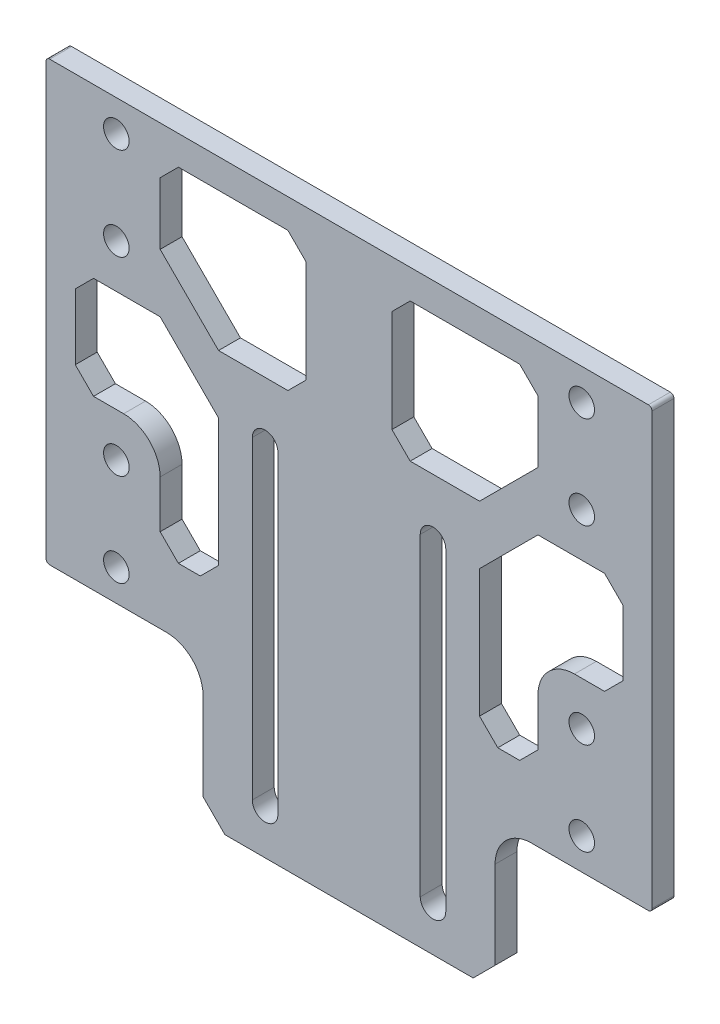
SolidWorks part; units mm, degrees
ref_plane "Plano frontal" through (0, 0, 0) normal (0, 0, 1) x (1, 0, 0)
ref_plane "Plano superior" through (0, 0, 0) normal (0, 1, 0) x (1, 0, 0)
ref_plane "Plano direito" through (0, 0, 0) normal (1, 0, 0) x (0, 0, -1)
sketch "Esboço1" plane through (0, 0, 0) normal (0, 0, 1) x (1, 0, 0)
  line L28 (-83, -60) -> (83, -60)
  line L29 (-83, -60) -> (-83, 60)
  line L30 (-83, 60) -> (83, 60)
  line L31 (83, -60) -> (83, 60)
  line L32 (-83, -60) -> (83, 60) construction
  line L33 (-83, 60) -> (83, -60) construction
  point P0 (0, 0)
  dimension "D1" = 120
  dimension "D2" = 166
extrude "Ressalto-extrusão1" add sketch "Esboço1" along normal blind 6
sketch "Esboço2" plane through (0, 0, 6) normal (0, 0, 1) x (1, 0, 0)
  circle A0 centre (-63.75, -51.4) radius 3.5
  circle A1 centre (-63.75, -26) radius 3.5
  circle A2 centre (-63.75, 26) radius 3.5
  circle A3 centre (-63.75, 51.4) radius 3.5
  circle A4 centre (63.75, -51.4) radius 3.5
  circle A5 centre (63.75, -26) radius 3.5
  circle A6 centre (63.75, 26) radius 3.5
  circle A7 centre (63.75, 51.4) radius 3.5
  dimension "D1" = 7
extrude "Corte-extrusão1" cut sketch "Esboço2" against normal through all
sketch "Esboço3" plane through (0, 0, 6) normal (0, 0, 1) x (1, 0, 0)
  line L0 (-83, -60) -> (83, -60) construction
  line L1 (-40, -20) -> (40, -20)
  line L2 (-40, -20) -> (-40, -100)
  line L3 (-40, -100) -> (40, -100)
  line L4 (40, -20) -> (40, -100)
  line L5 (-40, -20) -> (40, -100) construction
  line L6 (-40, -100) -> (40, -20) construction
  point P0 (0, -60)
  dimension "D1" = 80
  dimension "D2" = 80
extrude "Ressalto-extrusão2" add sketch "Esboço3" against normal through all
fillet "Filete1" radius 10 2 edges at (40, -60, 3) (-40, -60, 3)
chamfer "Chanfro1" distance 6 angle 45 2 edges at (-40, -100, 3) (40, -100, 3)
sketch "Esboço4" plane through (0, 0, 6) normal (0, 0, 1) x (1, 0, 0)
  line L0 (-23, -2) -> (-23, -88) construction
  line L1 (-19.5, -2) -> (-19.5, -88)
  line L2 (-26.5, -2) -> (-26.5, -88)
  line L3 (23, -2) -> (23, -88) construction
  line L4 (26.5, -2) -> (26.5, -88)
  line L5 (19.5, -2) -> (19.5, -88)
  line L6 (-23, -45) -> (23, -45) construction
  line L7 (0, -45) -> (0, 0) construction
  line L8 (-34, -100) -> (34, -100) construction
  arc A0 (-19.5, -2) -> (-26.5, -2) centre (-23, -2) ccw
  arc A1 (-26.5, -88) -> (-19.5, -88) centre (-23, -88) ccw
  arc A2 (26.5, -2) -> (19.5, -2) centre (23, -2) ccw
  arc A3 (19.5, -88) -> (26.5, -88) centre (23, -88) ccw
  point P2 (-23, -45)
  point P7 (23, -45)
  dimension "D2" = 3.5
  dimension "D1" = 46
  dimension "D3" = 86
  dimension "D4" = 12
extrude "Corte-extrusão2" cut sketch "Esboço4" against normal blind 10
sketch "Esboço5" plane through (0, 0, 6) normal (0, 0, 1) x (1, 0, 0)
  line L0 (-51.75, 52) -> (-51.75, 14)
  line L1 (-51.75, -42) -> (-35.75, -42)
  line L2 (-35.75, -42) -> (-35.75, 14)
  line L3 (-35.75, 14) -> (-11.75, 14)
  line L4 (-11.75, 14) -> (-11.75, 52)
  line L5 (-11.75, 52) -> (-51.75, 52)
  line L6 (83, 60) -> (-83, 60) construction
  line L7 (-51.75, -14) -> (-51.75, -42)
  line L8 (-51.75, 14) -> (-75, 14)
  line L9 (-75, 14) -> (-75, -14)
  line L10 (-75, -14) -> (-51.75, -14)
  line L11 (-83, 60) -> (-83, -60) construction
  line L12 (0, 0) -> (0, 60) construction
  line L13 (75, -14) -> (51.75, -14)
  line L14 (75, 14) -> (75, -14)
  line L15 (51.75, 14) -> (75, 14)
  line L16 (51.75, -14) -> (51.75, -42)
  line L17 (11.75, 52) -> (51.75, 52)
  line L18 (11.75, 14) -> (11.75, 52)
  line L19 (35.75, 14) -> (11.75, 14)
  line L20 (35.75, -42) -> (35.75, 14)
  line L21 (51.75, -42) -> (35.75, -42)
  line L22 (51.75, 52) -> (51.75, 14)
  circle A0 centre (-63.75, 26) radius 3.5 construction
  circle A1 centre (-63.75, -26) radius 3.5 construction
  dimension "D1" = 40
  dimension "D2" = 8
  dimension "D3" = 12
  dimension "D4" = 8
  dimension "D5" = 12
  dimension "D6" = 12
  dimension "D7" = 16
  dimension "D8" = 28
extrude "Corte-extrusão3" cut sketch "Esboço5" against normal through all
sketch "Esboço6" plane through (0, 0, 6) normal (0, 0, 1) x (1, 0, 0)
  line L0 (-51.75, 14) -> (-35.75, -2)
  line L1 (-35.75, -42) -> (-35.75, 14) construction
  line L2 (-35.75, 14) -> (-51.75, 30)
  line L3 (-51.75, 52) -> (-51.75, 14) construction
  line L4 (-51.75, 30) -> (-51.75, 14)
  line L5 (-35.75, 14) -> (-35.75, -2)
  line L6 (-35.75, 14) -> (-11.75, 14) construction
  line L7 (0, 0) -> (0, 60) construction
  line L8 (83, 60) -> (-83, 60) construction
  line L9 (35.75, 14) -> (51.75, 30)
  line L10 (51.75, 30) -> (51.75, 14)
  line L11 (51.75, 14) -> (35.75, -2)
  line L12 (35.75, 14) -> (35.75, -2)
  dimension "D1" = 135
extrude "Ressalto-extrusão3" add sketch "Esboço6" against normal through all contours L5 L0 L4 L2 | L9 L10 L11 L12
fillet "Filete2" radius 10 2 edges at (51.75, -14, 3) (-51.75, -14, 3)
chamfer "Chanfro2" distance 5 angle 45 14 edges at (-11.75, 14, 3) (-51.75, 52, 3) (-11.75, 52, 3) (11.75, 14, 3) (11.75, 52, 3) (51.75, 52, 3) (75, 14, 3) (75, -14, 3) (35.75, -42, 3) (-51.75, -42, 3) (-35.75, -42, 3) (-75, 14, 3) (-75, -14, 3) (51.75, -42, 3)
fillet "Filete3" radius 1 4 edges at (83, 60, 3) (-83, 60, 3) (-83, -60, 3) (83, -60, 3)
